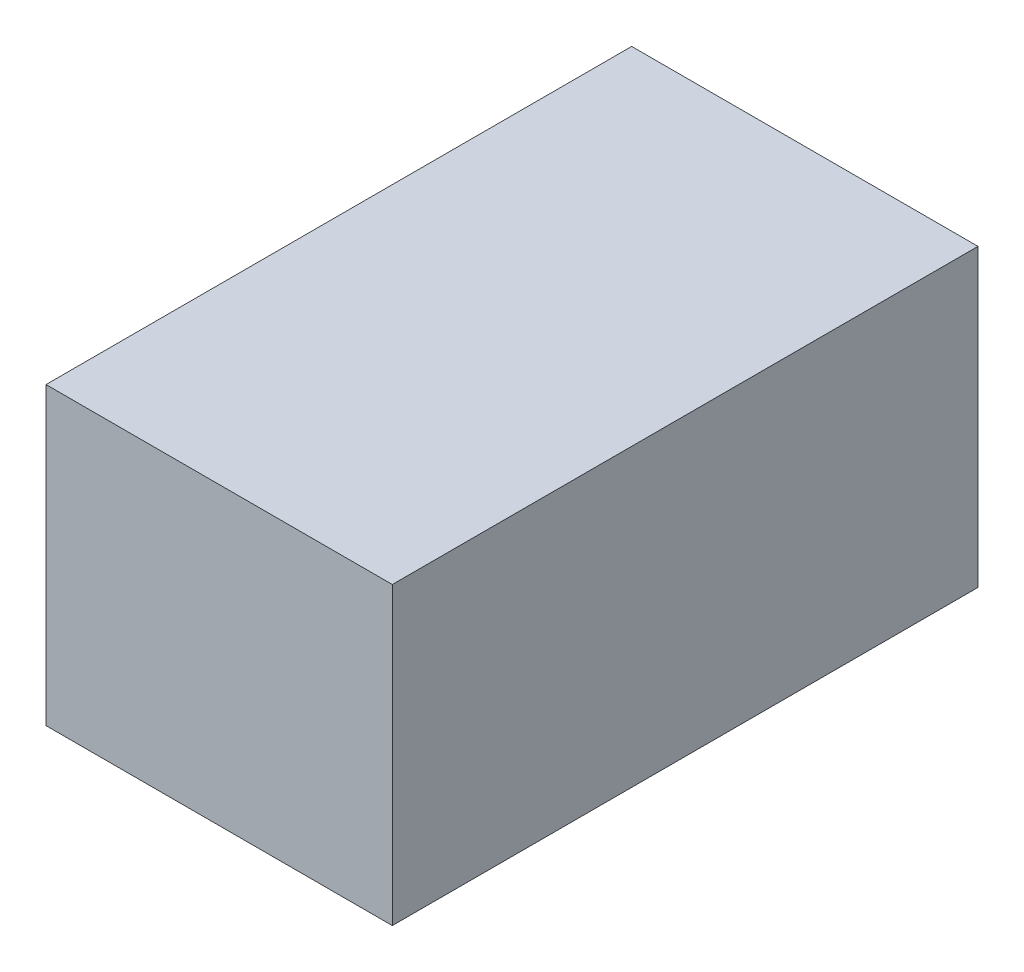
SolidWorks part; units mm, degrees
ref_plane "Front Plane" through (0, 0, 0) normal (0, 0, 1) x (1, 0, 0)
ref_plane "Top Plane" through (0, 0, 0) normal (0, 1, 0) x (1, 0, 0)
ref_plane "Right Plane" through (0, 0, 0) normal (1, 0, 0) x (0, 0, -1)
sketch "Sketch1" plane through (0, 0, 0) normal (0, 1, 0) x (1, 0, 0)
  line L1 (-34, 57.5) -> (34, 57.5)
  line L2 (-34, 57.5) -> (-34, -57.5)
  line L3 (-34, -57.5) -> (34, -57.5)
  line L4 (34, 57.5) -> (34, -57.5)
  line L5 (-34, 57.5) -> (34, -57.5) construction
  line L6 (-34, -57.5) -> (34, 57.5) construction
  point P0 (0, 0)
  dimension "D1" = 115
  dimension "D2" = 68
extrude "Boss-Extrude1" add sketch "Sketch1" along normal blind 58
